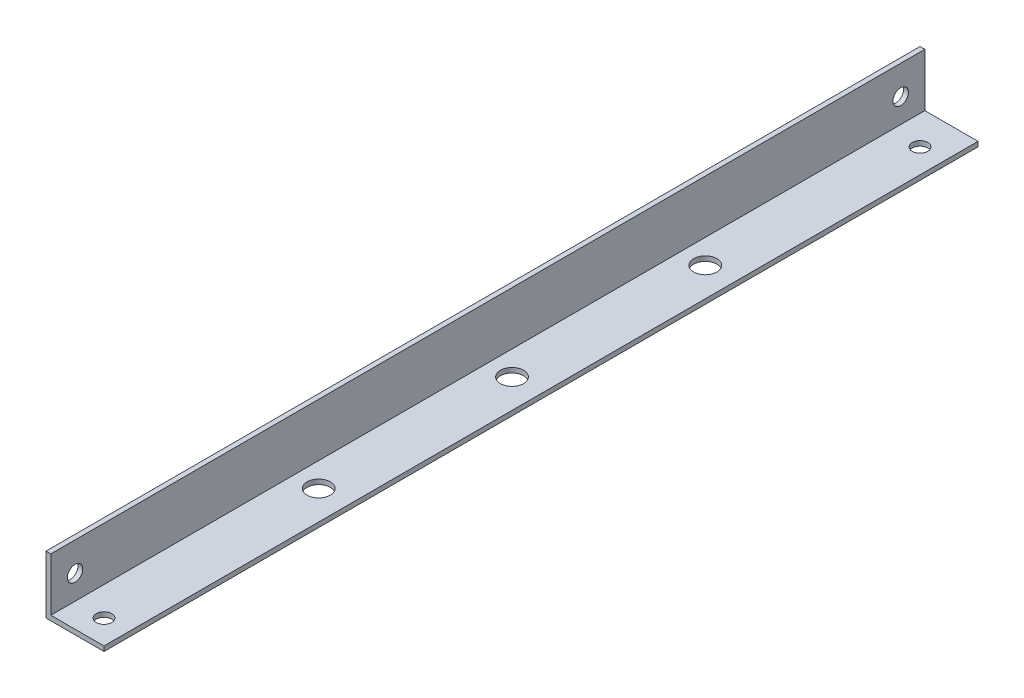
SolidWorks part; units mm, degrees
ref_plane "Front Plane" through (0, 0, 0) normal (0, 0, 1) x (1, 0, 0)
ref_plane "Top Plane" through (0, 0, 0) normal (0, 1, 0) x (1, 0, 0)
ref_plane "Right Plane" through (0, 0, 0) normal (1, 0, 0) x (0, 0, -1)
sketch "Sketch1" plane through (0, 0, 0) normal (0, 0, 1) x (1, 0, 0)
  line L0 (0, 2.5) -> (0, 30)
  line L1 (0, 2.5) -> (0, 0)
  line L2 (0, 30) -> (2.5, 30)
  line L3 (2.5, 2.5) -> (30, 2.5)
  line L4 (30, 2.5) -> (30, 0)
  line L5 (30, 0) -> (0, 0)
  line L6 (2.5, 30) -> (2.5, 2.5)
  dimension "D1" = 2.5
  dimension "D2" = 2.5
  dimension "D3" = 30
  dimension "D4" = 30
extrude "Boss-Extrude1" add sketch "Sketch1" along normal mid plane 452.2
sketch "Sketch2" plane through (0, 2.5, 0) normal (0, 1, 0) x (1, 0, 0)
  line L0 (-107.4419, 0) -> (128.0895, 0) construction
  line L1 (30, 226.1) -> (2.5, 226.1) construction
  line L2 (30, -226.1) -> (30, 226.1) construction
  line L3 (0, 226.1) -> (30, 226.1) construction
  line L8 (30, -226.1) -> (2.5, -226.1) construction
  circle A0 centre (17.5, 208.6) radius 4
  circle A1 centre (17.5, -213.6) radius 4
  circle A2 centre (15, -100) radius 6
  circle A3 centre (15, 100) radius 6
  circle A4 centre (15, 0) radius 6
  point P9 (15, 226.1)
  point P22 (30, 0)
  dimension "D2" = 8
  dimension "D6" = 100
  dimension "D10" = 12
  dimension "D11" = 12
  dimension "D12" = 12
  dimension "D3" = 12.5
  dimension "D4" = 17.5
  dimension "D5" = 12.5
  dimension "D7" = 100
  dimension "D8" = 12.5
  dimension "D9" = 226.1
  dimension "D13" = 15
extrude "Cut-Extrude1" cut sketch "Sketch2" against normal through all
sketch "Sketch3" plane through (2.5, 0, 0) normal (1, 0, 0) x (0, 0, -1)
  line L0 (0, 0) -> (0, 127.2663) construction
  line L1 (-226.1, 2.5) -> (-226.1, 30) construction
  line L2 (-226.1, 30) -> (226.1, 30) construction
  circle A0 centre (-213.6, 15) radius 4
  circle A1 centre (213.6, 15) radius 4
  dimension "D1" = 8
  dimension "D2" = 12.5
  dimension "D3" = 15
extrude "Cut-Extrude2" cut sketch "Sketch3" against normal through all
